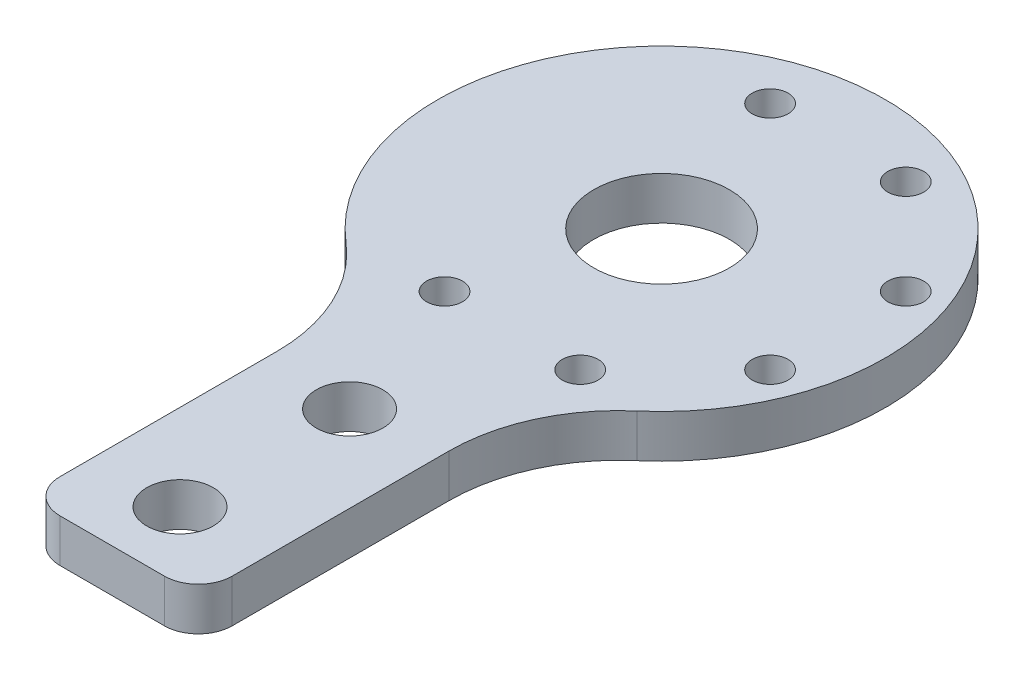
SolidWorks part; units mm, degrees
material "1060 Alloy"
ref_plane "Front Plane" through (0, 0, 0) normal (0, 0, 1) x (1, 0, 0)
ref_plane "Top Plane" through (0, 0, 0) normal (0, 1, 0) x (1, 0, 0)
ref_plane "Right Plane" through (0, 0, 0) normal (1, 0, 0) x (0, 0, -1)
sketch "Sketch1" plane through (0, 0, 0) normal (0, 1, 0) x (1, 0, 0)
  line L0 (-12.7, -81) -> (12.7, -81)
  line L1 (12.7, -81) -> (12.7, -30.4583)
  line L2 (-12.7, -81) -> (-12.7, -30.4583)
  line L3 (0, -81) -> (0, -46) construction
  arc A0 (12.7, -30.4583) -> (-12.7, -30.4583) centre (0, 0) ccw
  point P5 (0, -81)
  point P9 (0, -71)
  dimension "D2" = 66
  dimension "D1" = 25.4
  dimension "D3" = 46
  dimension "D4" = 25
  dimension "D5" = 10
extrude "Boss-Extrude1" add sketch "Sketch1" along normal blind 6.35 contours A0 L2 L0 L1
sketch "Sketch2" plane through (0, 0, 0) normal (0, -1, 0) x (1, 0, 0)
  point P14 (12, -24)
  point P16 (-8, -24)
  point P19 (2, 0)
  point P21 (26, 10)
  point P22 (26, -10)
  point P23 (-22, -10)
  point P24 (-22, 10)
  point P25 (-8, 24)
  point P26 (12, 24)
  point P27 (2, 0)
  dimension "D2" = 10
  dimension "D1" = 20
  dimension "D3" = 2
  dimension "D4" = 24
  dimension "D5" = 4
sketch "Sketch5" plane through (0, 0, 0) normal (0, -1, 0) x (1, 0, 0)
  circle A0 centre (0, 0) radius 10
  dimension "D1" = 20
extrude "Cut-Extrude1" cut sketch "Sketch5" against normal through all
hole_wizard "3/8 Clearance Hole1" positions "Sketch13" profile "Sketch14" hole size "3/8" standard "ANSI Inch" end condition through all
sketch "Sketch13" plane through (0, 0, 0) normal (0, -1, 0) x (-1, 0, 0)
  point P0 (0, -46)
  point P3 (0, -71)
sketch "Sketch14" plane through (0, 0, 46) normal (1, 0, 0) x (0, 0, -1)
  line L0 (0, 0) -> (0, 6.35)
  line L1 (0, 6.35) -> (4.9022, 6.35)
  line L2 (4.9022, 6.35) -> (4.9022, 0)
  line L5 (4.9022, 0) -> (0, 0)
  line L11 (0, -6.35) -> (0, 107.95) construction
  dimension "Thru Hole Dia." = 9.8044
  dimension "Thru Hole Depth" = 6.35
fillet "Fillet1" radius 25 2 edges at (-12.7, 3.175, 30.4583) (12.7, 3.175, 30.4583)
hole_wizard "M5 Clearance Hole1" positions "Sketch18" profile "Sketch19" hole size "M5" standard "ANSI Metric" end condition through all
sketch "Sketch18" plane through (0, 0, 0) normal (0, -1, 0) x (-1, 0, 0)
  point P0 (8, 24)
  point P3 (-12, 24)
  point P6 (-26, 10)
  point P9 (-26, -10)
  point P12 (-12, -24)
  point P15 (8, -24)
sketch "Sketch19" plane through (-8, 0, -24) normal (1, 0, 0) x (0, 0, -1)
  line L0 (0, 0) -> (0, 6.35)
  line L1 (0, 6.35) -> (2.65, 6.35)
  line L2 (2.65, 6.35) -> (2.65, 0)
  line L5 (2.65, 0) -> (0, 0)
  line L11 (0, -6.35) -> (0, 107.95) construction
  dimension "Thru Hole Dia." = 5.3
  dimension "Thru Hole Depth" = 6.35
fillet "Fillet2" radius 5 2 edges at (-12.7, 3.175, 81) (12.7, 3.175, 81)
